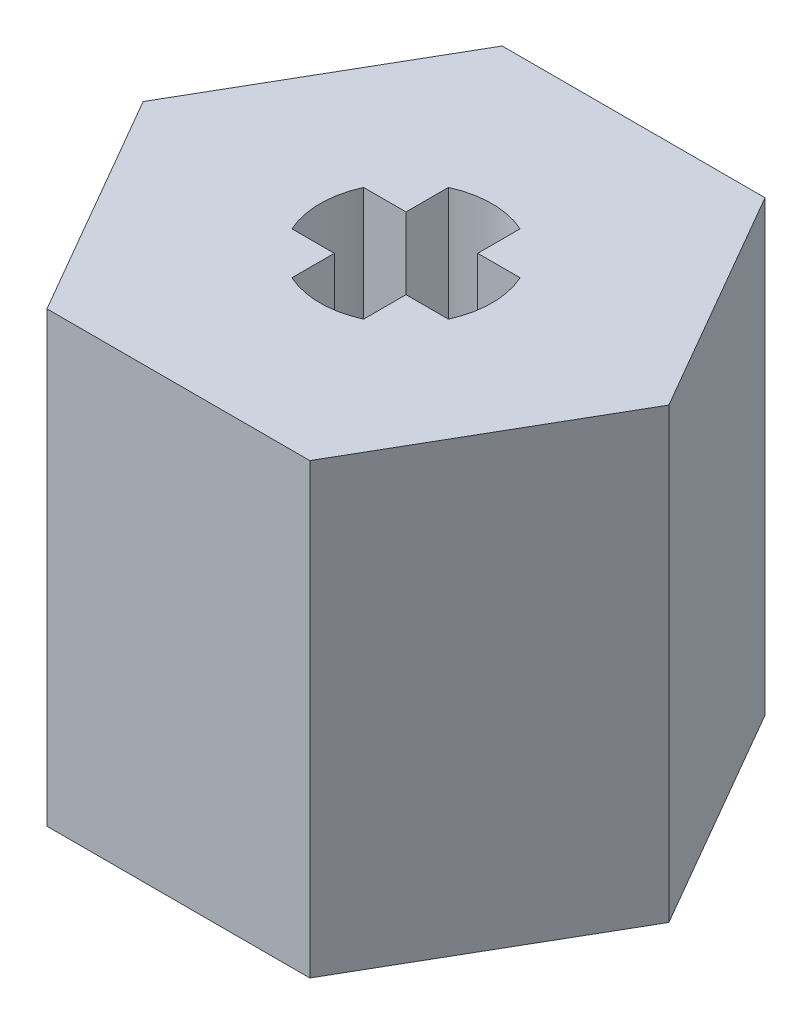
SolidWorks part; units mm, degrees
ref_plane "Front" through (0, 0, 0) normal (0, 0, 1) x (1, 0, 0)
ref_plane "Top" through (0, 0, 0) normal (0, 1, 0) x (1, 0, 0)
ref_plane "Right" through (0, 0, 0) normal (1, 0, 0) x (0, 0, -1)
sketch "Sketch1" plane through (0, 0, 0) normal (0, 1, 0) x (1, 0, 0)
  line L0 (0, 0) -> (1, 0)
  line L7 (7.3323, 0) -> (3.6662, 6.35)
  line L8 (3.6662, 6.35) -> (-3.6662, 6.35)
  line L9 (-3.6662, 6.35) -> (-7.3323, 0)
  line L10 (-7.3323, 0) -> (-3.6662, -6.35)
  line L11 (-3.6662, -6.35) -> (3.6662, -6.35)
  line L12 (3.6662, -6.35) -> (7.3323, 0)
  line L13 (1, 0) -> (1, 2.1817)
  line L14 (0, 0) -> (-1, 0)
  line L15 (-1, 0) -> (-1, 2.1817)
  line L16 (-1, 0) -> (-1, -2.1817)
  line L17 (1, 0) -> (1, -2.1817)
  line L18 (-1, 0) -> (-1, -2.1817)
  line L19 (1, 0) -> (1, -2.1817)
  line L20 (0, 0) -> (0, 1)
  line L21 (0, 1) -> (2.1817, 1)
  line L22 (0, 0) -> (0, -1)
  line L23 (0, -1) -> (2.1817, -1)
  line L24 (0, -1) -> (-2.1817, -1)
  line L25 (0, 1) -> (-2.1817, 1)
  circle A0 centre (0, 0) radius 6.35 construction
  circle A1 centre (0, 0) radius 2.4
  dimension "D1" = 1
  dimension "D3" = 1
  dimension "D2" = 1
  dimension "D4" = 1
extrude "Boss-Extrude1" add sketch "Sketch1" along normal blind 12.5 contours L11 L12 L7 L8 L9 L10 A1 | L15 A1 L25 | L24 A1 L18 | L19 A1 L23 | L21 A1 L13
